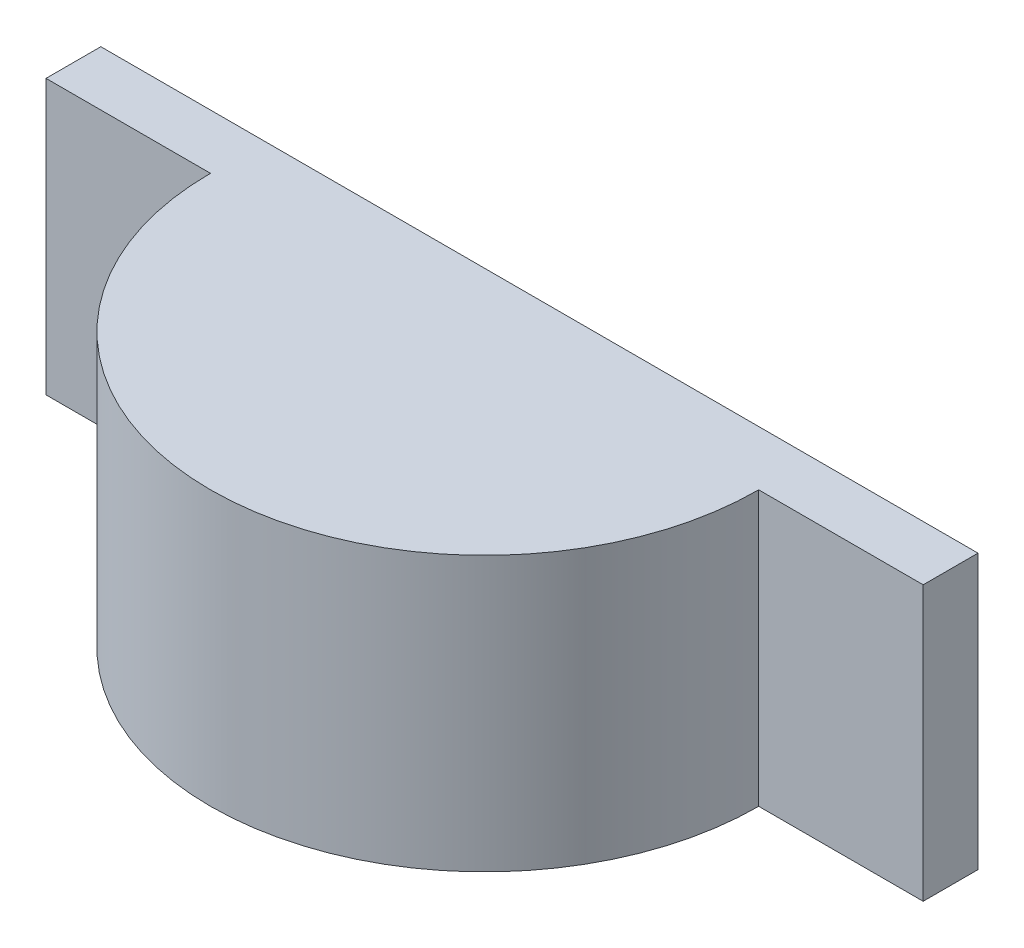
SolidWorks part; units mm, degrees
ref_plane "Alzado" through (0, 0, 0) normal (0, 0, 1) x (1, 0, 0)
ref_plane "Planta" through (0, 0, 0) normal (0, 1, 0) x (1, 0, 0)
ref_plane "Vista lateral" through (0, 0, 0) normal (1, 0, 0) x (0, 0, -1)
sketch "Croquis1" plane through (0, 0, 0) normal (0, 0, 1) x (1, 0, 0)
  line L1 (0, 0) -> (160, 0)
  line L2 (0, 0) -> (0, 50)
  line L3 (0, 50) -> (160, 50)
  line L4 (160, 0) -> (160, 50)
  dimension "D1" = 50
  dimension "D2" = 160
extrude "Saliente-Extruir1" add sketch "Croquis1" along normal blind 10
sketch "Croquis3" plane through (0, 0, 0) normal (0, -1, 0) x (1, 0, 0)
  line L0 (0, 10) -> (160, 10) construction
  line L1 (30, 10) -> (130, 10)
  arc A0 (130, 10) -> (30, 10) centre (80, 10) ccw
  dimension "D1" = 100
extrude "Saliente-Extruir2" add sketch "Croquis3" against normal up to surface (50 mm away) up to face at (80, 50, 5)
ref_plane "Plano1" through (0, 0, 70) normal (0, 0, 1) x (1, 0, 0)
